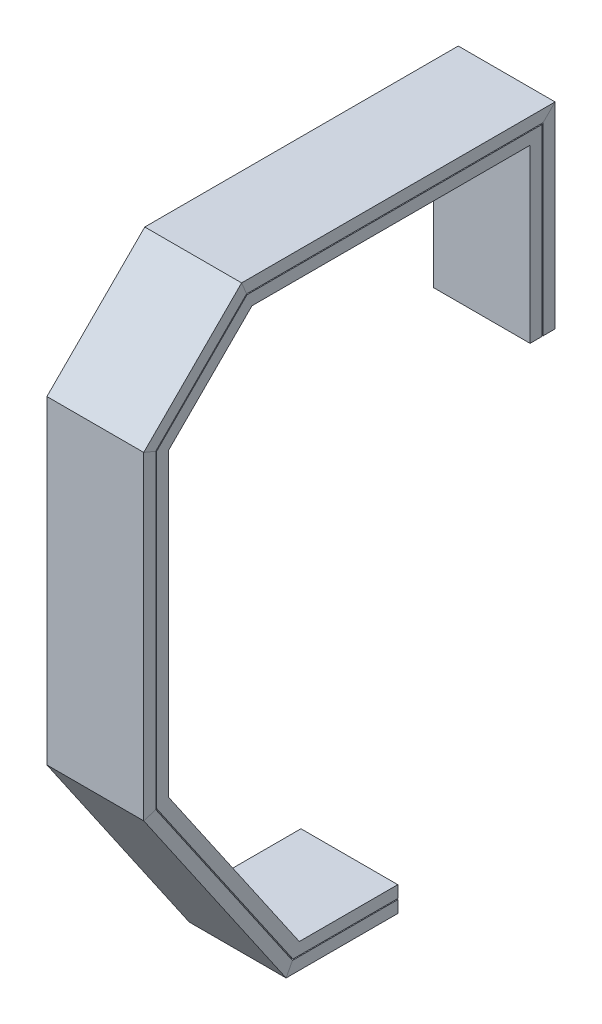
SolidWorks part; units mm, degrees
ref_plane "Alzado" through (0, 0, 0) normal (0, 0, 1) x (1, 0, 0)
ref_plane "Planta" through (0, 0, 0) normal (0, 1, 0) x (1, 0, 0)
ref_plane "Vista lateral" through (0, 0, 0) normal (1, 0, 0) x (0, 0, -1)
sketch "Croquis1" plane through (0, 0, 0) normal (0, 1, 0) x (1, 0, 0)
  line L1 (-25.4, 3.155) -> (25.4, 3.155)
  line L2 (-25.4, 3.155) -> (-25.4, -3.155)
  line L3 (-25.4, -3.155) -> (25.4, -3.155)
  line L4 (25.4, 3.155) -> (25.4, -3.155)
  line L5 (-25.4, 3.155) -> (25.4, -3.155) construction
  line L6 (-25.4, -3.155) -> (25.4, 3.155) construction
  point P0 (0, 0)
  dimension "D1" = 6.31
  dimension "D2" = 50.8
sketch3d "Croquis3D1"
  line L0 (0, 0, 0) -> (0, 100, 0)
  line L1 (0, 100, 0) -> (0, 100, 160)
  line L2 (0, -114.6075, 209.4975) -> (0, -114.6075, 136.3011) construction
  line L3 (0, 100, 160) -> (0, 50.5025, 209.4975)
  line L4 (0, 50.5025, 209.4975) -> (0, -114.6075, 209.4975)
  line L5 (0, -114.6075, 136.3011) -> (0, -221.1775, 136.3011) construction
  line L6 (0, -221.1775, 136.3011) -> (0, -221.1775, 79.3711)
  line L7 (0, -221.1775, 136.3011) -> (0, -114.6075, 209.4975)
  dimension "D1" = 100
  dimension "D2" = 160
  dimension "D3" = 165.11
  dimension "D4" = 135
  dimension "D5" = 106.57
  dimension "D6" = 56.93
  dimension "D7" = 70
sweep "Barrer1" add profiles "Croquis1" path "Croquis3D1"
sketch "Croquis2" plane through (-25.4, 0, 0) normal (-1, 0, 0) x (0, 0, 1)
  line L0 (3.155, 0) -> (3.155, 96.845) construction
  line L1 (3.155, 96.845) -> (158.6932, 96.845) construction
  line L2 (158.6932, 96.845) -> (206.3425, 49.1957) construction
  line L3 (206.3425, 49.1957) -> (206.3425, -113.6283) construction
  line L4 (206.3425, -113.6283) -> (134.6405, -218.0225) construction
  line L5 (134.6405, -218.0225) -> (79.3711, -218.0225) construction
  line L6 (3.655, 0) -> (3.655, 96.345)
  line L7 (3.655, 96.345) -> (158.486, 96.345)
  line L8 (158.486, 96.345) -> (205.8425, 48.9886)
  line L9 (205.8425, 48.9886) -> (205.8425, -113.4732)
  line L10 (205.8425, -113.4732) -> (134.3774, -217.5225)
  line L11 (134.3774, -217.5225) -> (79.3711, -217.5225)
  line L12 (9.965, 0) -> (9.965, 90.035)
  line L13 (9.965, 90.035) -> (155.8724, 90.035)
  line L14 (155.8724, 90.035) -> (199.5325, 46.3749)
  line L15 (199.5325, 46.3749) -> (199.5325, -111.5149)
  line L16 (199.5325, -111.5149) -> (131.0563, -211.2125)
  line L17 (131.0563, -211.2125) -> (79.3711, -211.2125)
  line L18 (79.3711, -211.2125) -> (79.3711, -217.5225)
  line L19 (3.655, 0) -> (9.965, 0)
  dimension "D1" = 0.5
  dimension "D2" = 6.31
extrude "Saliente-Extruir1" add sketch "Croquis2" against normal blind 50.8 separate body
